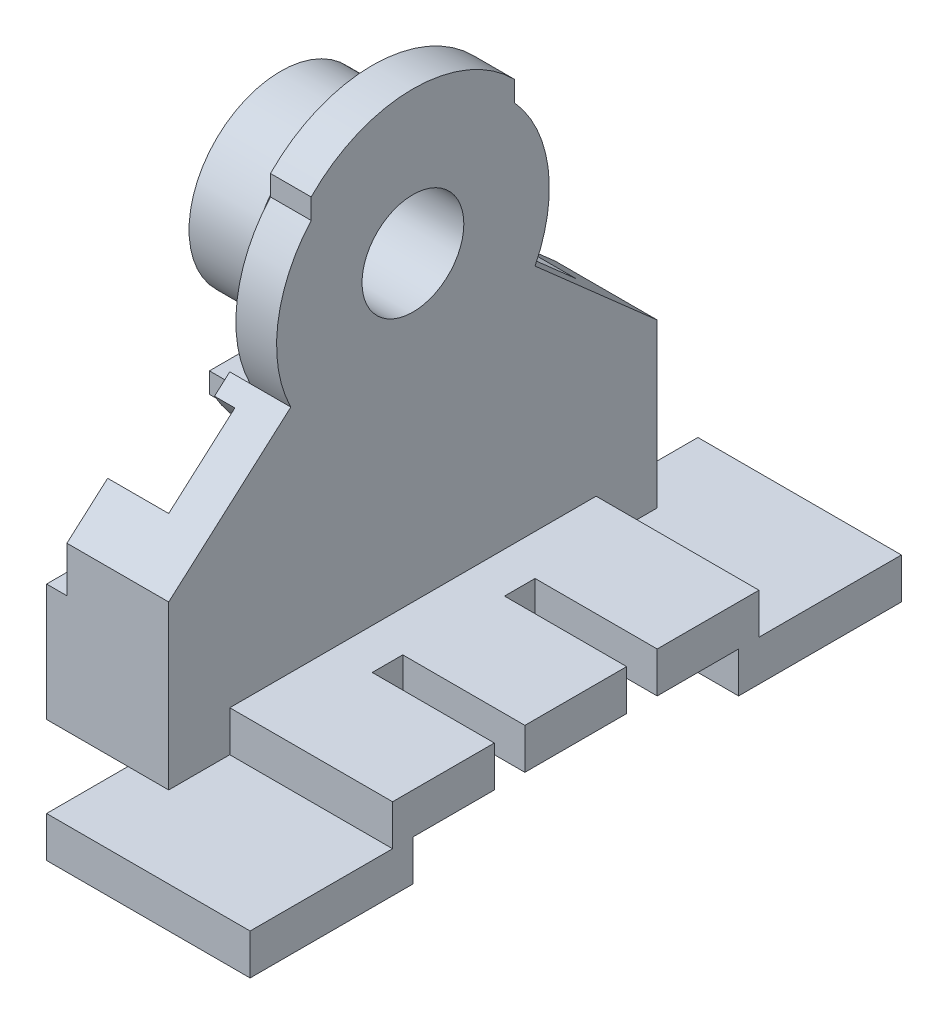
SolidWorks part; units mm, degrees
material "ABS generico"
ref_plane "Piano frontale" through (0, 0, 0) normal (0, 0, 1) x (1, 0, 0)
ref_plane "Piano superiore" through (0, 0, 0) normal (0, 1, 0) x (1, 0, 0)
ref_plane "Piano destro" through (0, 0, 0) normal (1, 0, 0) x (0, 0, -1)
sketch "Schizzo2" plane through (0, 0, 0) normal (0, 1, 0) x (1, 0, 0)
  line L0 (-36.6564, 0) -> (36.6564, 0) construction
  line L1 (36.6564, 0) -> (0, 0) construction
  line L2 (0, 32.0729) -> (0, -32.0729) construction
  line L3 (0, 16) -> (10, 16)
  line L8 (0, -8) -> (10, -8)
  line L9 (0, -8) -> (0, -16)
  line L10 (0, -16) -> (10, -16)
  line L11 (10, -8) -> (10, -16)
  line L12 (10, 8) -> (10, 16)
  line L13 (0, 8) -> (10, 8)
  line L14 (0, 8) -> (0, 16)
  point P4 (0, 0)
  point P9 (0, 0)
  dimension "D1" = 8
  dimension "D2" = 10
  dimension "D3" = 8
extrude "Estrusione-Estrusione1" add sketch "Schizzo2" along normal blind 2
ref_plane "Piano1" through (0, 2, 0) normal (0, 1, 0) x (1, 0, 0)
sketch "Schizzo3" plane through (0, 2, 0) normal (0, 1, 0) x (1, 0, 0)
  line L0 (0, 0) -> (17.4665, 0) construction
  line L1 (0, 2.5) -> (0, -2.5)
  line L2 (4, -4) -> (10, -4)
  line L3 (0, -4) -> (0, -9)
  line L4 (0, -9) -> (10, -9)
  line L5 (0, -8) -> (0, -16)
  line L6 (0, -16) -> (10, -16)
  line L7 (10, -16) -> (10, -8)
  line L8 (10, -8) -> (0, -8)
  line L9 (0, -8) -> (0, -16) construction
  line L10 (0, -16) -> (10, -16) construction
  line L11 (10, -16) -> (10, -8) construction
  line L12 (10, -8) -> (0, -8) construction
  line L13 (10, -4) -> (10, -9)
  line L14 (4, 2.5) -> (10, 2.5)
  line L15 (10, 2.5) -> (10, -2.5)
  line L16 (4, -2.5) -> (10, -2.5)
  line L17 (0, 9) -> (0, 4)
  line L18 (0, 9) -> (10, 9)
  line L19 (10, 9) -> (10, 4)
  line L20 (4, 4) -> (10, 4)
  line L21 (0, 8) -> (10, 8) construction
  line L22 (4, -4) -> (4, -2.5)
  line L23 (4, 2.5) -> (4, 4)
  line L24 (0, -4) -> (0, -2.5)
  line L25 (0, 2.5) -> (0, 4)
  line L27 (10, 8) -> (10, 16) construction
  line L28 (0, 16) -> (0, 8) construction
  dimension "D2" = 1
  dimension "D3" = 5
  dimension "D5" = 1
  dimension "D6" = 4
  dimension "D1" = 0
  dimension "D4" = 3
extrude "Estrusione-Estrusione2" add sketch "Schizzo3" along normal blind 2 contours L13 L2 L3 L4 | L25 L1 L24 L2 L22 L16 L15 L14 L23 L20 | L17 L20 L19 L18
sketch "Schizzo5" plane through (0, 2, 0) normal (0, 1, 0) x (1, 0, 0)
  line L0 (0, -9) -> (10, -9) construction
  line L1 (-4, 12) -> (2, 12)
  line L2 (-4, 12) -> (-4, 10)
  line L3 (-4, -12) -> (2, -12)
  line L4 (2, 12) -> (2, -12)
  line L5 (0, 9) -> (10, 9) construction
  line L6 (0, 16) -> (0, 9) construction
  line L7 (-4, -10) -> (0, -10)
  line L8 (0, -9) -> (0, -16) construction
  line L9 (0, -10) -> (0, 10)
  line L10 (0, 10) -> (-4, 10)
  line L11 (-4, -10) -> (-4, -12)
  point P14 (2, 9)
  point P21 (2, -9)
  dimension "D1" = 3
  dimension "D2" = 3
  dimension "D3" = 6
  dimension "D4" = 2
  dimension "D5" = 2
  dimension "D6" = 2
extrude "Estrusione-Estrusione3" add sketch "Schizzo5" along normal blind 26 from surface at 0 starting at face at (5, 2, 12.5)
sketch "Schizzo6" plane through (0, 0, 0) normal (1, 0, 0) x (0, 0, -1)
  line L0 (-12, 10) -> (-12, 28)
  line L1 (-12, 28) -> (12, 28)
  line L2 (12, 28) -> (12, 10)
  line L4 (-12, 10) -> (-6, 15.2915)
  line L5 (0, 0) -> (0, 6.0705) construction
  line L8 (-12, 2) -> (-9, 2)
  line L9 (-9, 2) -> (-9, 4)
  line L10 (-9, 4) -> (9, 4)
  line L11 (9, 4) -> (9, 2)
  line L12 (9, 2) -> (12, 2)
  line L13 (12, 2) -> (12, 28)
  line L14 (12, 28) -> (-12, 28)
  line L15 (-12, 28) -> (-12, 2)
  line L16 (-12, 2) -> (-9, 2) construction
  line L17 (-9, 2) -> (-9, 4) construction
  line L18 (-9, 4) -> (9, 4) construction
  line L19 (9, 4) -> (9, 2) construction
  line L20 (9, 2) -> (12, 2) construction
  line L21 (12, 10) -> (12, 28) construction
  line L22 (12, 28) -> (-12, 28) construction
  line L23 (-12, 28) -> (-12, 10) construction
  line L25 (-5, 23.7329) -> (-5, 22.7329)
  line L26 (5, 23.7329) -> (5, 22.7329)
  line L27 (0, 7.7) -> (0, -7.7) construction
  line L28 (12, 10) -> (6, 15.2915)
  arc A7 (-5, 22.7329) -> (-6, 15.2915) centre (0, 18.2731) ccw
  arc A8 (6, 15.2915) -> (5, 22.7329) centre (0, 18.2731) ccw
  arc A9 (5, 23.7329) -> (-5, 23.7329) centre (0, 18.834) ccw
  dimension "D5" = 7
  dimension "D7" = 10
  dimension "D8" = 6.7
  dimension "D3" = 12
  dimension "D2" = 8
  dimension "D4" = 8
  dimension "D6" = 1
  dimension "D1" = 0
extrude "Taglio-Estrusione1" cut sketch "Schizzo6" against normal through all both and the other way through all
sketch "Schizzo8" plane through (0, 0, 0) normal (1, 0, 0) x (0, 0, -1)
  circle A0 centre (0, 18.834) radius 2.5
  arc A2 (5, 23.7329) -> (-5, 23.7329) centre (0, 18.834) ccw construction
  dimension "D1" = 5
extrude "Taglio-Estrusione2" cut sketch "Schizzo8" against normal through all both and the other way through all
sketch "Schizzo9" plane through (0, 0, 0) normal (0, 0, 1) x (1, 0, 0)
  line L1 (4, 2) -> (10, 2) construction
  line L2 (4, 2) -> (10, 2) construction
  line L3 (8, 2) -> (6.5, 2)
  line L4 (6.5, 2) -> (6.5, 0.5)
  line L5 (6.5, 0.5) -> (8, 2)
  dimension "D1" = 2
  dimension "D2" = 1.5
  dimension "D3" = 45
extrude "Estrusione-Estrusione4" add sketch "Schizzo9" along normal mid plane 2
sketch "Schizzo11" plane through (0, 0, 0) normal (1, 0, 0) x (0, 0, -1)
  line L0 (-8, 2) -> (8, 2) construction
  line L1 (4, 11.834) -> (-4, 11.834)
  line L2 (4, 11.834) -> (4, 12.834)
  line L3 (4, 12.834) -> (-4, 12.834)
  line L4 (-4, 11.834) -> (-4, 12.834)
  line L5 (4, 11.834) -> (-4, 12.834) construction
  line L6 (4, 12.834) -> (-4, 11.834) construction
  line L7 (-8, 2) -> (8, 2) construction
  circle A0 centre (0, 18.834) radius 2.5 construction
  circle A1 centre (0, 18.834) radius 2.5 construction
  point P3 (0, 12.334)
  point P10 (0, 16.334)
  dimension "D3" = 8
  dimension "D1" = 1
  dimension "D2" = 3.5
extrude "Estrusione-Estrusione5" add sketch "Schizzo11" against normal blind 4 from surface at 0 starting at face at (0, 18.834, -2.5)
sketch "Schizzo12" plane through (0, 0, 0) normal (1, 0, 0) x (0, 0, -1)
  circle A0 centre (0, 18.834) radius 4.5
  circle A1 centre (0, 18.834) radius 2.5 construction
  circle A2 centre (0, 18.834) radius 2.5
  point P3 (-2.5, 18.834)
  point P4 (-4.5, 18.834)
  dimension "D1" = 2
extrude "Estrusione-Estrusione6" add sketch "Schizzo12" against normal blind 4.5 from surface at 0 starting at face at (0, 8.2725, 0)
sketch "Schizzo13" plane through (0, 0, 0) normal (1, 0, 0) x (0, 0, -1)
  circle A0 centre (0, 18.834) radius 4.5 construction
  circle A1 centre (0, 18.834) radius 4.5
  circle A2 centre (0, 18.834) radius 5
  point P3 (4.5, 18.834)
  point P5 (5, 18.834)
  dimension "D1" = 0.5
extrude "Estrusione-Estrusione7" add sketch "Schizzo13" against normal blind 1 from surface at 0 starting at face at (0, 18.834, -4.5)
sketch "Schizzo14" plane through (0, 0, 0) normal (0, 0, 1) x (1, 0, 0)
  line L0 (-4, 10) -> (-4, 2) construction
  line L1 (-4, 10) -> (-4, 2) construction
  line L3 (-4, 11.7638) -> (-3, 11.7638)
  line L4 (-4, 11.7638) -> (-4, 7.7638)
  line L5 (-4, 7.7638) -> (-3, 7.7638)
  line L6 (-3, 11.7638) -> (-3, 7.7638)
  dimension "D1" = 4
  dimension "D2" = 1
extrude "Taglio-Estrusione3" cut sketch "Schizzo14" against normal through all from surface at 12 starting at face at (-0.8, 5.2, 12)
sketch "Schizzo17" plane through (0, 0, 0) normal (1, 0, 0) x (0, 0, -1)
  line L4 (6, 15.2915) -> (10, 11.7638) construction
  line L6 (-10, 11.7638) -> (-6, 15.2915) construction
  line L12 (-4, 11.834) -> (-4, 12.834) construction
  line L14 (4, 12.834) -> (4, 11.834) construction
  line L16 (6, 15.2915) -> (6.75, 14.6301)
  line L17 (-6.75, 14.6301) -> (-6, 15.2915)
  line L18 (-4, 11.834) -> (-4, 12.834)
  line L19 (4, 12.834) -> (4, 11.834)
  arc A1 (-5, 22.7329) -> (-6, 15.2915) centre (0, 18.2731) ccw construction
  arc A5 (4, 12.834) -> (6, 15.2915) centre (-0.4459, 18.4947) ccw
  arc A6 (4, 11.834) -> (6.75, 14.6301) centre (0.0614, 18.458) ccw
  arc A7 (-4, 12.834) -> (-6, 15.2915) centre (0.4459, 18.4947) cw
  arc A8 (-4, 11.834) -> (-6.75, 14.6301) centre (-0.0614, 18.458) cw
  arc A11 (6, 15.2915) -> (5, 22.7329) centre (0, 18.2731) ccw construction
  dimension "D1" = 1
  dimension "D2" = 1
extrude "Estrusione-Estrusione8" add sketch "Schizzo17" against normal blind 1 from surface at 0 starting at face at (0, 18.834, -5)
